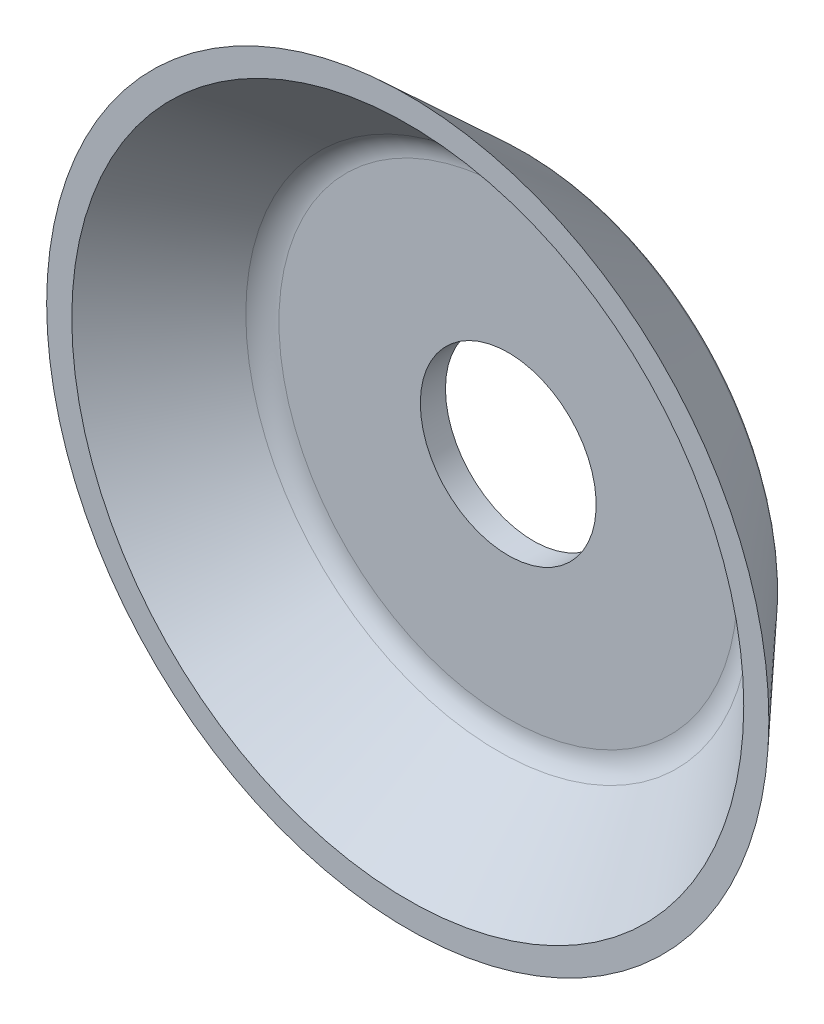
SolidWorks part; units mm, degrees
material "Простая углеродистая сталь"
ref_plane "Спереди" through (0, 0, 0) normal (0, 0, 1) x (1, 0, 0)
ref_plane "Сверху" through (0, 0, 0) normal (0, 1, 0) x (1, 0, 0)
ref_plane "Справа" through (0, 0, 0) normal (1, 0, 0) x (0, 0, -1)
sketch "Эскиз4" plane through (0, 0, 0) normal (1, 0, 0) x (0, 0, -1)
  line L0 (0, 2.8) -> (0, 7.8)
  line L1 (0, 7.8) -> (-4, 11.5)
  line L2 (-4, 11.5) -> (-4, 10.7)
  line L3 (-4, 10.7) -> (-0.8, 7.74)
  line L4 (-0.8, 7.74) -> (-0.8, 2.8)
  line L5 (-0.8, 2.8) -> (0, 2.8)
  line L6 (0, 0) -> (-16.4888, 0) construction
  dimension "D1" = 2.8
  dimension "D2" = 5
  dimension "D3" = 11.5
  dimension "D4" = 4
  dimension "D5" = 0.8
  dimension "D6" = 0.8
revolve "Повернуть1" add sketch "Эскиз4" angle 360 about L6
fillet "Скругление1" radius 1 2 edges at (-7.74, 0, 0.8) (-7.8, 0, 0)
